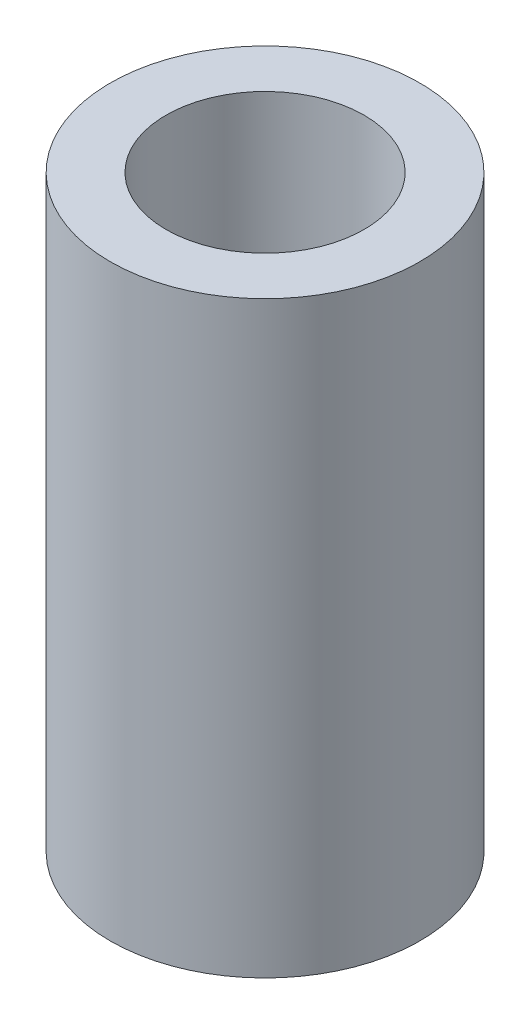
SolidWorks part; units mm, degrees
ref_plane "Alzado" through (0, 0, 0) normal (0, 0, 1) x (1, 0, 0)
ref_plane "Planta" through (0, 0, 0) normal (0, 1, 0) x (1, 0, 0)
ref_plane "Vista lateral" through (0, 0, 0) normal (1, 0, 0) x (0, 0, -1)
sketch "Croquis1" plane through (0, 0, 0) normal (0, 1, 0) x (1, 0, 0)
  circle A0 centre (0, 0) radius 1.6
  circle A1 centre (0, 0) radius 2.5
  dimension "D1" = 3.2
  dimension "D2" = 5
extrude "Saliente-Extruir1" add sketch "Croquis1" along normal blind 9.5
